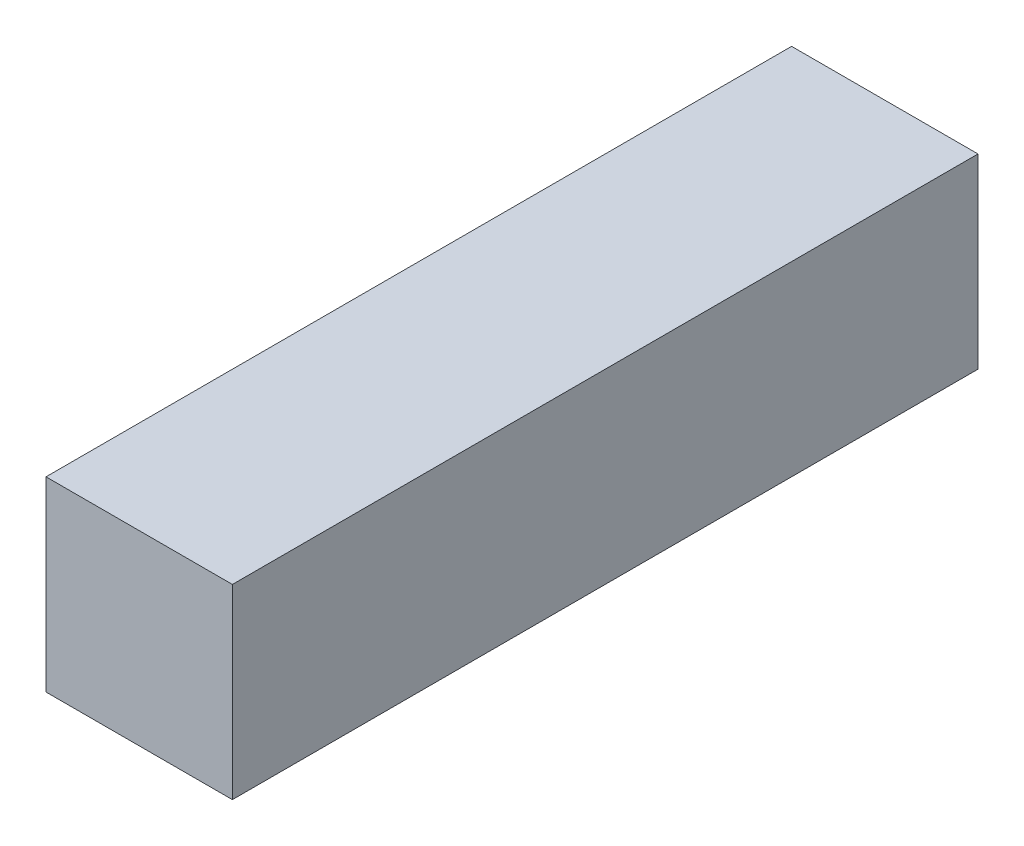
SolidWorks part; units mm, degrees
ref_plane "Front Plane" through (0, 0, 0) normal (0, 0, 1) x (1, 0, 0)
ref_plane "Top Plane" through (0, 0, 0) normal (0, 1, 0) x (1, 0, 0)
ref_plane "Right Plane" through (0, 0, 0) normal (1, 0, 0) x (0, 0, -1)
sketch "Sketch1" plane through (0, 0, 0) normal (0, 0, 1) x (1, 0, 0)
  line L1 (-1.5, -1.5) -> (1.5, -1.5)
  line L2 (-1.5, -1.5) -> (-1.5, 1.5)
  line L3 (-1.5, 1.5) -> (1.5, 1.5)
  line L4 (1.5, -1.5) -> (1.5, 1.5)
  line L5 (-1.5, -1.5) -> (1.5, 1.5) construction
  line L6 (-1.5, 1.5) -> (1.5, -1.5) construction
  point P0 (0, 0)
  dimension "D1" = 3
  dimension "D2" = 3
extrude "Boss-Extrude1" add sketch "Sketch1" along normal blind 12
